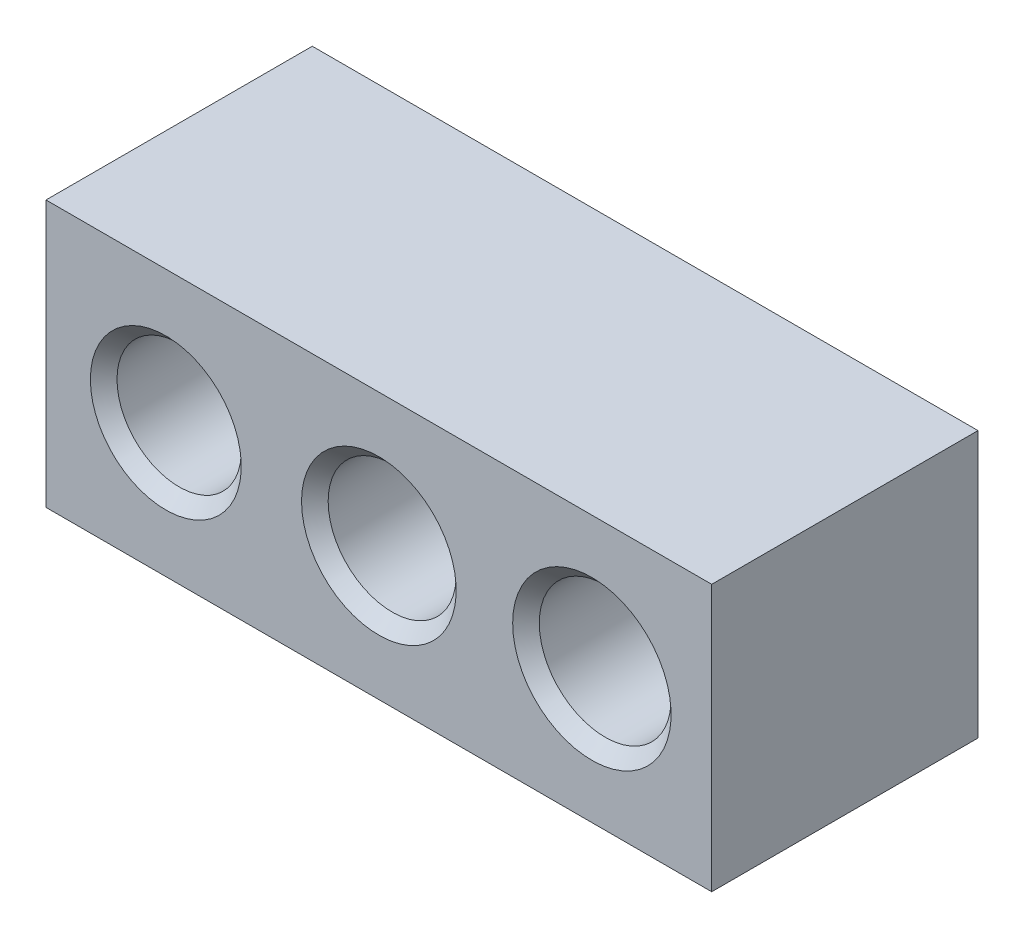
SolidWorks part; units mm, degrees
ref_plane "Front Plane" through (0, 0, 0) normal (0, 0, 1) x (1, 0, 0)
ref_plane "Top Plane" through (0, 0, 0) normal (0, 1, 0) x (1, 0, 0)
ref_plane "Right Plane" through (0, 0, 0) normal (1, 0, 0) x (0, 0, -1)
sketch "Sketch1" plane through (0, 0, 0) normal (0, 0, 1) x (1, 0, 0)
  line L1 (1.7, 1.7) -> (-1.7, 1.7) construction
  line L2 (1.7, 1.7) -> (1.7, -1.7) construction
  line L3 (1.7, -1.7) -> (-1.7, -1.7) construction
  line L4 (-1.7, 1.7) -> (-1.7, -1.7) construction
  line L5 (1.7, 1.7) -> (-1.7, -1.7) construction
  line L6 (1.7, -1.7) -> (-1.7, 1.7) construction
  line L7 (-9.65, -1.65) -> (-6.35, -1.65) construction
  line L8 (-9.65, -1.65) -> (-9.65, 1.65) construction
  line L9 (-9.65, 1.65) -> (-6.35, 1.65) construction
  line L10 (-6.35, -1.65) -> (-6.35, 1.65) construction
  line L11 (-9.65, -1.65) -> (-6.35, 1.65) construction
  line L12 (-9.65, 1.65) -> (-6.35, -1.65) construction
  line L13 (6.25, -1.75) -> (9.75, -1.75) construction
  line L14 (6.25, -1.75) -> (6.25, 1.75) construction
  line L15 (6.25, 1.75) -> (9.75, 1.75) construction
  line L16 (9.75, -1.75) -> (9.75, 1.75) construction
  line L17 (6.25, -1.75) -> (9.75, 1.75) construction
  line L18 (6.25, 1.75) -> (9.75, -1.75) construction
  line L19 (-12.5, -5) -> (12.5, -5)
  line L20 (-12.5, -5) -> (-12.5, 5)
  line L21 (-12.5, 5) -> (12.5, 5)
  line L22 (12.5, -5) -> (12.5, 5)
  line L23 (-12.5, -5) -> (12.5, 5) construction
  line L24 (-12.5, 5) -> (12.5, -5) construction
  circle A0 centre (0, 0) radius 2.4042
  circle A1 centre (-8, 0) radius 2.3335
  circle A2 centre (8, 0) radius 2.4749
  point P0 (0, 0)
  point P8 (-8, 0)
  point P13 (8, 0)
  dimension "D2" = 3.3
  dimension "D4" = 8
  dimension "D1" = 3.4
  dimension "D3" = 3.5
  dimension "D5" = 8
  dimension "D6" = 10
  dimension "D7" = 25
extrude "Boss-Extrude1" add sketch "Sketch1" along normal blind 10
chamfer "Chamfer1" distance 0.5 angle 45 3 edges at (10.4749, 0, 10) (2.4042, 0, 10) (-5.6665, 0, 10)
